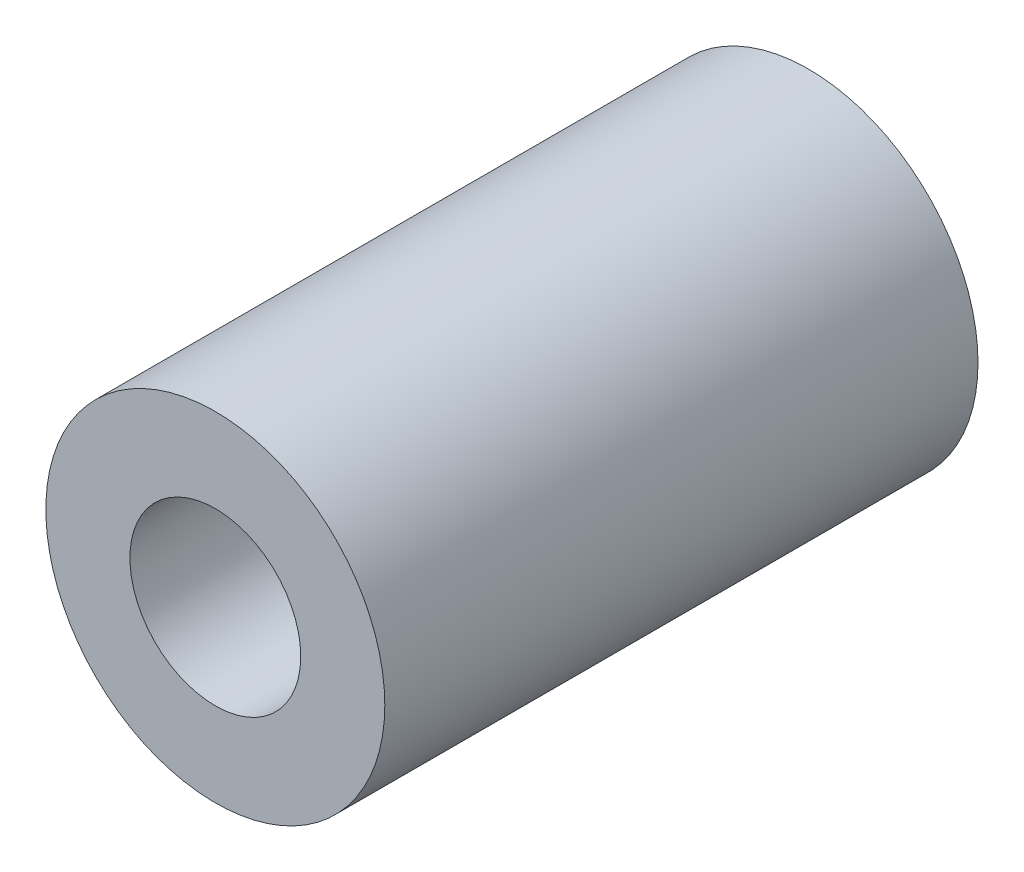
SolidWorks part; units mm, degrees
ref_plane "Front Plane" through (0, 0, 0) normal (0, 0, 1) x (1, 0, 0)
ref_plane "Top Plane" through (0, 0, 0) normal (0, 1, 0) x (1, 0, 0)
ref_plane "Right Plane" through (0, 0, 0) normal (1, 0, 0) x (0, 0, -1)
sketch "Sketch2" plane through (0, 0, 0) normal (0, 0, 1) x (1, 0, 0)
  circle A0 centre (0, 0) radius 3.2004
  circle A1 centre (0, 0) radius 6.35
extrude "Boss-Extrude1" add sketch "Sketch2" along normal mid plane 22.225
